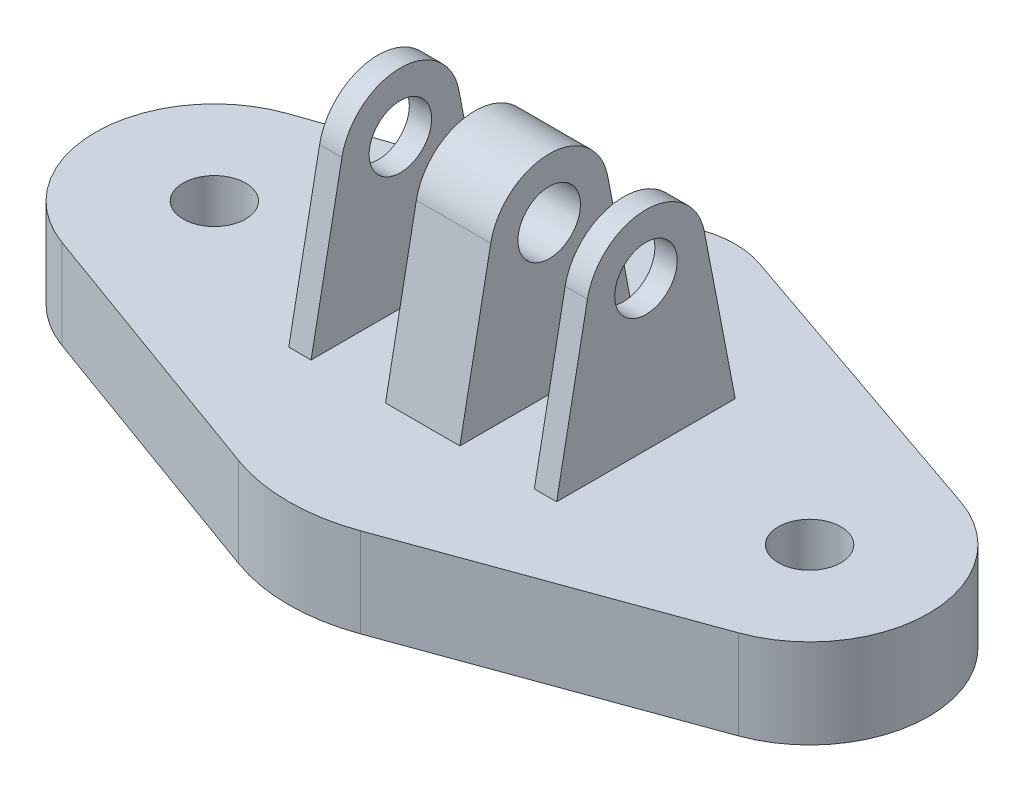
SolidWorks part; units mm, degrees
ref_plane "Front Plane" through (0, 0, 0) normal (0, 0, 1) x (1, 0, 0)
ref_plane "Top Plane" through (0, 0, 0) normal (0, 1, 0) x (1, 0, 0)
ref_plane "Right Plane" through (0, 0, 0) normal (1, 0, 0) x (0, 0, -1)
sketch "Sketch1" plane through (0, 0, 0) normal (0, 1, 0) x (1, 0, 0)
  line L0 (22.604, 7.5644) -> (1.953, 14.6733)
  line L5 (0, -39.2644) -> (0, 49.8899) construction
  line L6 (22.7281, -7.5205) -> (4.0921, -14.2807)
  line L7 (0, 15) -> (0, -15)
  arc A0 (1.953, 14.6733) -> (0, 15) centre (0, 9) ccw
  arc A1 (22.604, 7.5644) -> (22.7281, -7.5205) centre (20, 0) cw
  arc A2 (4.0921, -14.2807) -> (0, -15) centre (0, -3) cw
  circle A3 centre (20, 0) radius 2.1
  point P0 (0, 0)
  point P13 (0, 0)
  point P14 (28.641, -7.0303)
  dimension "D2" = 4.2
  dimension "D3" = 8
  dimension "D4" = 6
  dimension "D5" = 12
  dimension "D1" = 20
  dimension "D6" = 30
extrude "Boss-Extrude1" add sketch "Sketch1" along normal blind 6
mirror "Mirror1" about plane through (0, 6, -15) normal (1, 0, 0) of "Boss-Extrude1"
sketch "Sketch2" plane through (0, 0, 0) normal (1, 0, 0) x (0, 0, -1)
  line L0 (-6, 6) -> (-3.9278, 16.7567)
  line L1 (7.5644, 6) -> (-7.5205, 6) construction
  line L2 (3.9278, 16.7567) -> (6, 6)
  line L3 (6, 6) -> (-6, 6)
  arc A0 (-3.9278, 16.7567) -> (3.9278, 16.7567) centre (0, 16) cw
  circle A1 centre (0, 16) radius 2.1
  point P6 (0, 6)
  point P10 (0, 0)
  dimension "D1" = 4
  dimension "D2" = 4.2
  dimension "D3" = 12
  dimension "D4" = 10
extrude "Boss-Extrude2" add sketch "Sketch2" along normal mid plane 18
sketch "Sketch3" plane through (0, 0, 0) normal (0, 0, 1) x (1, 0, 0)
  line L0 (9, 20) -> (-9, 20) construction
  line L1 (-7.5, 34) -> (-2.5, 34)
  line L2 (-7.5, 34) -> (-7.5, 6)
  line L3 (-7.5, 6) -> (-2.5, 6)
  line L4 (-2.5, 34) -> (-2.5, 6)
  line L5 (-7.5, 34) -> (-2.5, 6) construction
  line L6 (-7.5, 6) -> (-2.5, 34) construction
  line L7 (-4.0921, 6) -> (-22.7281, 6) construction
  point P0 (-5, 20)
  dimension "D1" = 5
  dimension "D2" = 2.5
extrude "Cut-Extrude1" cut sketch "Sketch3" against normal through all both and the other way through all
mirror "Mirror2" about plane through (0, 0, 0) normal (1, 0, 0) of "Cut-Extrude1"
